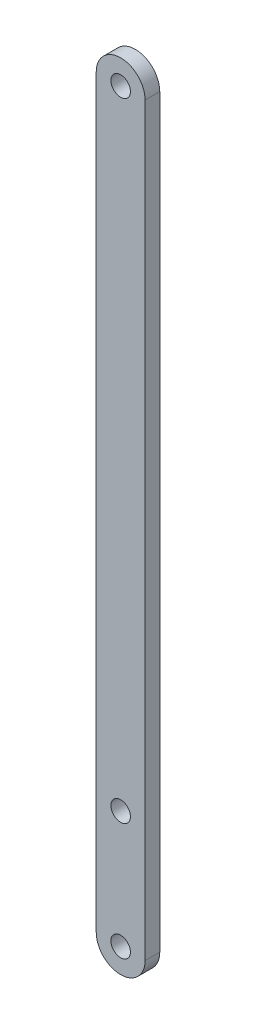
SolidWorks part; units mm, degrees
ref_plane "Front Plane" through (0, 0, 0) normal (0, 0, 1) x (1, 0, 0)
ref_plane "Top Plane" through (0, 0, 0) normal (0, 1, 0) x (1, 0, 0)
ref_plane "Right Plane" through (0, 0, 0) normal (1, 0, 0) x (0, 0, -1)
sketch "Sketch1" plane through (0, 0, 0) normal (0, 0, 1) x (1, 0, 0)
  line L0 (-5, 0) -> (-5, 152.5)
  line L1 (5, 152.5) -> (5, 0)
  circle A0 centre (0, 0) radius 2
  circle A1 centre (0, 152.5) radius 2
  circle A2 centre (0, 24) radius 2
  circle A3 centre (0, 0) radius 5
  circle A4 centre (0, 152.5) radius 5
  point P13 (0, 0)
  point P14 (-7.5, 0)
  line B0 (0, 0) -> (0, 152.5) construction
  dimension "D1" = 4
  dimension "D3" = 10
  dimension "D2" = 24
sketch_block_instance "Link 1-1"
sketch_block "Link 1" parameters "D1"=152.5
extrude "Boss-Extrude1" add sketch "Sketch1" along normal blind 3 contours A4 L0 A3 L1 A2 | A4 A1 | A3 A0
